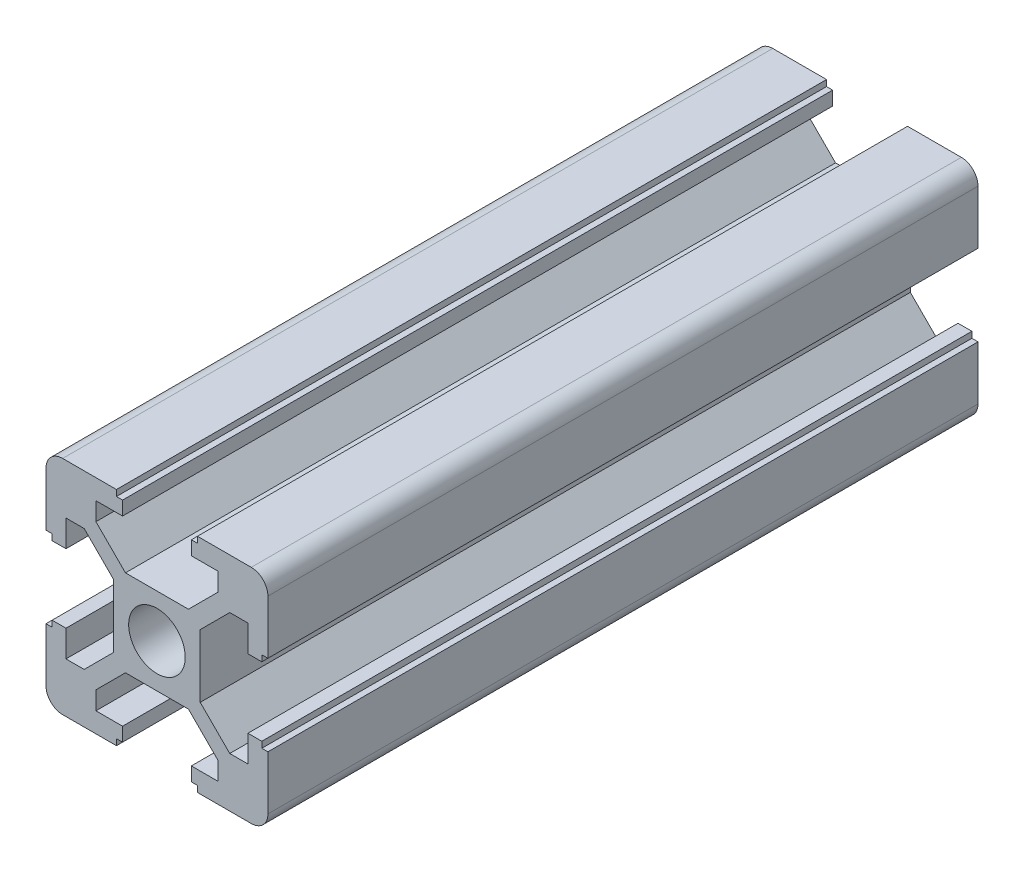
SolidWorks part; units mm, degrees
material "6063-T5"
ref_plane "前视基准面" through (0, 0, 0) normal (0, 0, 1) x (1, 0, 0)
ref_plane "上视基准面" through (0, 0, 0) normal (0, 1, 0) x (1, 0, 0)
ref_plane "右视基准面" through (0, 0, 0) normal (1, 0, 0) x (0, 0, -1)
sketch "草图1" plane through (0, 0, 0) normal (0, 0, 1) x (1, 0, 0)
  line L0 (-3.9, 2.8393) -> (-6.5607, 5.5)
  line L1 (-2.8393, 3.9) -> (2.8393, 3.9)
  line L2 (-3.9, 2.8393) -> (-3.9, -2.8393)
  line L3 (-2.8393, -3.9) -> (2.8393, -3.9)
  line L4 (3.9, 2.8393) -> (3.9, -2.8393)
  line L5 (-3.9, 3.9) -> (3.9, -3.9) construction
  line L6 (-3.9, -3.9) -> (3.9, 3.9) construction
  line L7 (-2.8393, 3.9) -> (-5.5, 6.5607)
  line L8 (-5.5, 6.5607) -> (-5.5, 8.2)
  line L9 (-5.5, 8.2) -> (-3.1, 8.2)
  line L10 (-3.1, 8.2) -> (-3.1, 9.45)
  line L11 (-3.1, 9.45) -> (-3.65, 9.45)
  line L12 (-3.65, 9.45) -> (-3.65, 10)
  line L13 (-3.65, 10) -> (-8.5, 10)
  line L14 (-6.5607, 5.5) -> (-8.2, 5.5)
  line L15 (-10, 3.65) -> (-10, 8.5)
  line L16 (-9.45, 3.65) -> (-10, 3.65)
  line L17 (-9.45, 3.1) -> (-9.45, 3.65)
  line L18 (-8.2, 3.1) -> (-9.45, 3.1)
  line L19 (-8.2, 5.5) -> (-8.2, 3.1)
  line L20 (2.8393, 3.9) -> (5.5, 6.5607)
  line L21 (3.9, 2.8393) -> (6.5607, 5.5)
  line L22 (6.5607, 5.5) -> (8.2, 5.5)
  line L23 (8.2, 5.5) -> (8.2, 3.1)
  line L24 (8.2, 3.1) -> (9.45, 3.1)
  line L25 (9.45, 3.1) -> (9.45, 3.65)
  line L26 (9.45, 3.65) -> (10, 3.65)
  line L27 (10, 3.65) -> (10, 8.5)
  line L28 (5.5, 6.5607) -> (5.5, 8.2)
  line L29 (3.65, 10) -> (8.5, 10)
  line L30 (3.65, 9.45) -> (3.65, 10)
  line L31 (3.1, 9.45) -> (3.65, 9.45)
  line L32 (3.1, 8.2) -> (3.1, 9.45)
  line L33 (5.5, 8.2) -> (3.1, 8.2)
  line L34 (3.9, -2.8393) -> (6.5607, -5.5)
  line L35 (2.8393, -3.9) -> (5.5, -6.5607)
  line L36 (5.5, -6.5607) -> (5.5, -8.2)
  line L37 (5.5, -8.2) -> (3.1, -8.2)
  line L38 (3.1, -8.2) -> (3.1, -9.45)
  line L39 (3.1, -9.45) -> (3.65, -9.45)
  line L40 (3.65, -9.45) -> (3.65, -10)
  line L41 (3.65, -10) -> (8.5, -10)
  line L42 (6.5607, -5.5) -> (8.2, -5.5)
  line L43 (10, -3.65) -> (10, -8.5)
  line L44 (9.45, -3.65) -> (10, -3.65)
  line L45 (9.45, -3.1) -> (9.45, -3.65)
  line L46 (8.2, -3.1) -> (9.45, -3.1)
  line L47 (8.2, -5.5) -> (8.2, -3.1)
  line L48 (-2.8393, -3.9) -> (-5.5, -6.5607)
  line L49 (-3.9, -2.8393) -> (-6.5607, -5.5)
  line L50 (-6.5607, -5.5) -> (-8.2, -5.5)
  line L51 (-8.2, -5.5) -> (-8.2, -3.1)
  line L52 (-8.2, -3.1) -> (-9.45, -3.1)
  line L53 (-9.45, -3.1) -> (-9.45, -3.65)
  line L54 (-9.45, -3.65) -> (-10, -3.65)
  line L55 (-10, -3.65) -> (-10, -8.5)
  line L56 (-5.5, -6.5607) -> (-5.5, -8.2)
  line L57 (-3.65, -10) -> (-8.5, -10)
  line L58 (-3.65, -9.45) -> (-3.65, -10)
  line L59 (-3.1, -9.45) -> (-3.65, -9.45)
  line L60 (-3.1, -8.2) -> (-3.1, -9.45)
  line L61 (-5.5, -8.2) -> (-3.1, -8.2)
  circle A0 centre (0, 0) radius 2.55
  arc A1 (-8.5, 10) -> (-10, 8.5) centre (-8.5, 8.5) ccw
  arc A2 (10, 8.5) -> (8.5, 10) centre (8.5, 8.5) ccw
  arc A3 (8.5, -10) -> (10, -8.5) centre (8.5, -8.5) ccw
  arc A4 (-10, -8.5) -> (-8.5, -10) centre (-8.5, -8.5) ccw
  point P74 (0, 0)
  dimension "D1" = 5.1
  dimension "D8" = 1.5
  dimension "D2" = 7.8
  dimension "D3" = 1.5
  dimension "D4" = 3.1
  dimension "D5" = 0.55
  dimension "D6" = 1.8
  dimension "D7" = 5.5
  dimension "D9" = 3.9
extrude "凸台-拉伸1" add sketch "草图1" along normal blind 64
